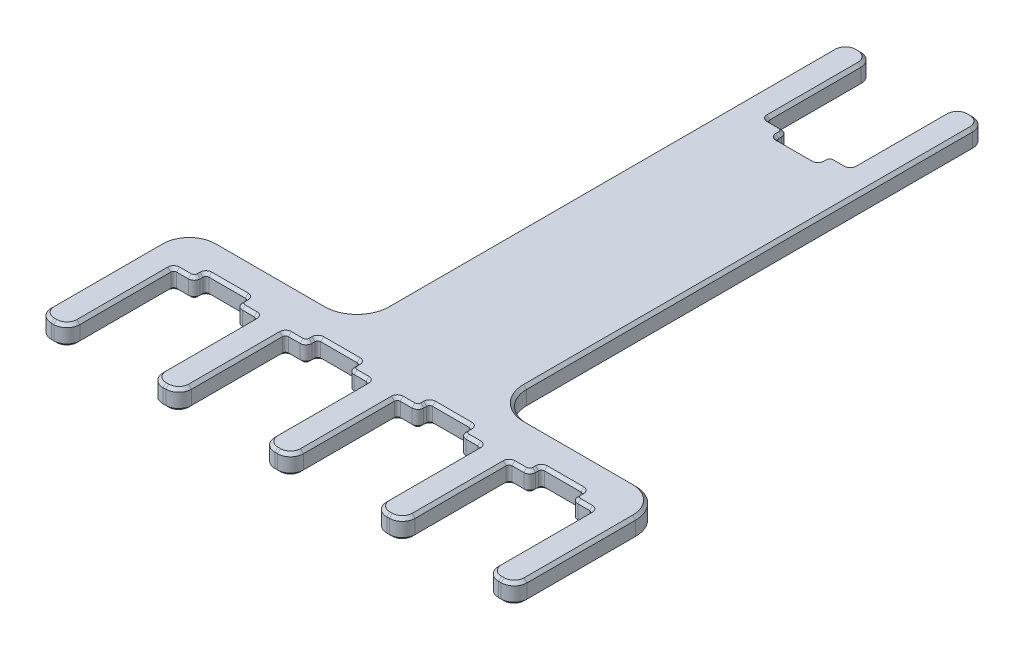
SolidWorks part; units mm, degrees
ref_plane "Front Plane" through (0, 0, 0) normal (0, 0, 1) x (1, 0, 0)
ref_plane "Top Plane" through (0, 0, 0) normal (0, 1, 0) x (1, 0, 0)
ref_plane "Right Plane" through (0, 0, 0) normal (1, 0, 0) x (0, 0, -1)
sketch "Sketch2" plane through (0, 0, 0) normal (0, 1, 0) x (1, 0, 0)
  line L0 (-5.2417, -1.575) -> (8.9583, -1.575)
  line L1 (-24.2917, -1.575) -> (-10.0917, -1.575)
  line L2 (-24.2917, -1.575) -> (-24.2917, -15.775)
  line L3 (-24.2917, -15.775) -> (-10.0917, -15.775)
  line L4 (-10.0917, -1.575) -> (-10.0917, -15.775)
  line L17 (-5.2417, -1.575) -> (-5.2417, -15.775)
  line L18 (-5.2417, -15.775) -> (8.9583, -15.775)
  line L19 (8.9583, -1.575) -> (8.9583, -15.775)
  line L20 (13.8083, -1.575) -> (28.0083, -1.575)
  line L21 (13.8083, -1.575) -> (13.8083, -15.775)
  line L22 (13.8083, -15.775) -> (28.0083, -15.775)
  line L23 (28.0083, -1.575) -> (28.0083, -15.775)
  line L24 (32.8583, -1.575) -> (47.0583, -1.575)
  line L25 (32.8583, -1.575) -> (32.8583, -15.775)
  line L26 (32.8583, -15.775) -> (47.0583, -15.775)
  line L27 (47.0583, -1.575) -> (47.0583, -15.775)
  line L28 (1.8583, -1.575) -> (1.8583, -15.775) construction
  line L29 (-17.1917, -15.775) -> (-17.1917, -1.575) construction
  dimension "D1" = 14.2
  dimension "D3" = 19.05
  dimension "D2" = 4
sketch "Sketch1" plane through (0, 0, 0) normal (0, 1, 0) x (1, 0, 0)
  line L0 (-29.1417, 5.925) -> (-0.5667, 5.925)
  line L1 (-0.5667, 5.925) -> (-0.5667, 89.125)
  line L3 (23.3333, 89.125) -> (23.3333, 5.925)
  line L4 (23.3333, 5.925) -> (51.9083, 5.925)
  line L5 (51.9083, 5.925) -> (51.9083, -19.775)
  line L6 (51.9083, -19.775) -> (-29.1417, -19.775)
  line L7 (-29.1417, -19.775) -> (-29.1417, 5.925)
  line L8 (-5.2417, -8.675) -> (-10.0917, -8.675) construction
  line L9 (-5.2417, -1.575) -> (-5.2417, -15.775) construction
  line L10 (-10.0917, -1.575) -> (-10.0917, -15.775) construction
  line L11 (47.0583, -8.675) -> (51.9083, -8.675) construction
  line L12 (47.0583, -1.575) -> (47.0583, -15.775) construction
  line L13 (-24.2917, -8.675) -> (-29.1417, -8.675) construction
  line L14 (-24.2917, -1.575) -> (-24.2917, -15.775) construction
  line L15 (18.4833, 70.925) -> (23.3333, 70.925) construction
  line L17 (-17.1917, -1.575) -> (-17.1917, -19.775) construction
  line L19 (-24.2917, -15.775) -> (-10.0917, -15.775) construction
  line L20 (-24.2917, -1.575) -> (-10.0917, -1.575) construction
  line L21 (4.2833, 89.125) -> (4.2833, 70.925)
  line L22 (4.2833, 70.925) -> (18.4833, 70.925)
  line L23 (18.4833, 70.925) -> (18.4833, 89.125)
  line L24 (-0.5667, 89.125) -> (4.2833, 89.125)
  line L25 (18.4833, 89.125) -> (23.3333, 89.125)
  line L26 (13.8083, -1.575) -> (28.0083, -1.575) construction
  line L27 (8.9583, -8.675) -> (13.8083, -8.675) construction
  line L28 (8.9583, -1.575) -> (8.9583, -15.775) construction
  line L29 (13.8083, -1.575) -> (13.8083, -15.775) construction
  line L30 (11.3833, 70.925) -> (11.3833, 89.125) construction
  line L31 (11.3833, -8.675) -> (11.3833, 70.925) construction
  line L32 (4.2833, 89.125) -> (18.4833, 89.125) construction
  dimension "D1" = 4
  dimension "D2" = 7.5
  dimension "D3" = 65
extrude "Boss-Extrude1" add sketch "Sketch1" along normal blind 3.4
sketch "Sketch3" plane through (0, 3.4, 0) normal (0, 1, 0) x (1, 0, 0)
  line L0 (-29.1417, -19.775) -> (51.9083, -19.775) construction
  line L2 (-24.2917, -1.575) -> (-24.2917, -19.775)
  line L3 (-24.2917, -19.775) -> (-10.0917, -19.775)
  line L4 (-10.0917, -1.575) -> (-10.0917, -19.775)
  line L5 (32.8583, -15.775) -> (47.0583, -15.775) construction
  line L7 (-5.2417, -1.575) -> (-5.2417, -19.775)
  line L8 (-5.2417, -19.775) -> (8.9583, -19.775)
  line L9 (8.9583, -1.575) -> (8.9583, -19.775)
  line L11 (13.8083, -1.575) -> (13.8083, -19.775)
  line L12 (13.8083, -19.775) -> (28.0083, -19.775)
  line L13 (28.0083, -1.575) -> (28.0083, -19.775)
  line L15 (32.8583, -1.575) -> (32.8583, -19.775)
  line L16 (32.8583, -19.775) -> (47.0583, -19.775)
  line L17 (47.0583, -1.575) -> (47.0583, -19.775)
  line L18 (-24.2917, -1.575) -> (-20.7917, -1.575)
  line L19 (-20.7917, -1.575) -> (-20.7917, 0.425)
  line L20 (-20.7917, 0.425) -> (-13.5917, 0.425)
  line L21 (-13.5917, 0.425) -> (-13.5917, -1.575)
  line L22 (-13.5917, -1.575) -> (-10.0917, -1.575)
  line L23 (-5.2417, -1.575) -> (-1.7417, -1.575)
  line L24 (-1.7417, -1.575) -> (-1.7417, 0.425)
  line L25 (-1.7417, 0.425) -> (5.4583, 0.425)
  line L26 (5.4583, 0.425) -> (5.4583, -1.575)
  line L27 (5.4583, -1.575) -> (8.9583, -1.575)
  line L28 (13.8083, -1.575) -> (17.3083, -1.575)
  line L29 (17.3083, -1.575) -> (17.3083, 0.425)
  line L30 (17.3083, 0.425) -> (24.5083, 0.425)
  line L31 (24.5083, 0.425) -> (24.5083, -1.575)
  line L32 (24.5083, -1.575) -> (28.0083, -1.575)
  line L33 (32.8583, -1.575) -> (36.3583, -1.575)
  line L34 (36.3583, -1.575) -> (36.3583, 0.425)
  line L35 (36.3583, 0.425) -> (43.5583, 0.425)
  line L36 (43.5583, 0.425) -> (43.5583, -1.575)
  line L37 (43.5583, -1.575) -> (47.0583, -1.575)
  line L38 (7.7833, 70.925) -> (7.7833, 68.925)
  line L39 (18.4833, 70.925) -> (4.2833, 70.925) construction
  line L40 (7.7833, 68.925) -> (14.9833, 68.925)
  line L41 (14.9833, 68.925) -> (14.9833, 70.925)
  line L42 (7.7833, 70.925) -> (14.9833, 70.925)
  line L43 (4.2833, 70.925) -> (7.7833, 70.925) construction
  line L44 (14.9833, 70.925) -> (18.4833, 70.925) construction
  dimension "D1" = 3.5
  dimension "D2" = 2
extrude "Cut-Extrude1" cut sketch "Sketch3" against normal blind 3.4
fillet "Fillet1" radius 5 4 edges at (-29.1417, 1.7, -5.925) (51.9083, 1.7, -5.925) (23.3333, 1.7, -5.925) (-0.5667, 1.7, -5.925)
fillet "Fillet2" radius 2.2 14 edges at (-0.5667, 1.7, -89.125) (4.2833, 1.7, -89.125) (18.4833, 1.7, -89.125) (23.3333, 1.7, -89.125) (51.9083, 1.7, 19.775) (47.0583, 1.7, 19.775) (32.8583, 1.7, 19.775) (28.0083, 1.7, 19.775) (13.8083, 1.7, 19.775) (8.9583, 1.7, 19.775) (-5.2417, 1.7, 19.775) (-10.0917, 1.7, 19.775) (-24.2917, 1.7, 19.775) (-29.1417, 1.7, 19.775)
fillet "Fillet3" radius 0.5 20 edges at (17.3083, 1.7, -0.425) (-1.7417, 1.7, -0.425) (-20.7917, 1.7, -0.425) (-13.5917, 1.7, -0.425) (5.4583, 1.7, -0.425) (24.5083, 1.7, -0.425) (36.3583, 1.7, -0.425) (43.5583, 1.7, -0.425) (47.0583, 1.7, 1.575) (32.8583, 1.7, 1.575) (13.8083, 1.7, 1.575) (28.0083, 1.7, 1.575) (8.9583, 1.7, 1.575) (-5.2417, 1.7, 1.575) (-10.0917, 1.7, 1.575) (-24.2917, 1.7, 1.575) (7.7833, 1.7, -68.925) (14.9833, 1.7, -68.925) (18.4833, 1.7, -70.925) (4.2833, 1.7, -70.925)
fillet "Fillet4" radius 1 10 edges at (-13.5917, 1.7, 1.575) (-1.7417, 1.7, 1.575) (5.4583, 1.7, 1.575) (17.3083, 1.7, 1.575) (24.5083, 1.7, 1.575) (36.3583, 1.7, 1.575) (43.5583, 1.7, 1.575) (-20.7917, 1.7, 1.575) (14.9833, 1.7, -70.925) (7.7833, 1.7, -70.925)
chamfer "Chamfer1" distance 0.5 192 edges at (-1.7417, 0, 0.325) (-1.5952, 0, -0.2786) (-2.0346, 0, 1.2821) (1.8583, 0, -0.425) (-3.7417, 0, 1.575) (5.3119, 0, -0.2786) (-5.0952, 0, 1.7214) (5.4583, 0, 0.325) (-5.2417, 0, 9.825) (5.7512, 0, 1.2821) (-5.886, 0, 19.1306) (7.4583, 0, 1.575) (-7.6667, 0, 19.775) (8.8119, 0, 1.7214) (-9.4473, 0, 19.1306) (8.9583, 0, 9.825) (-10.0917, 0, 9.825) (9.6027, 0, 19.1306) (-10.2381, 0, 1.7214) (11.3833, 0, 19.775) (-11.5917, 0, 1.575) (13.164, 0, 19.1306) (-13.2988, 0, 1.2821) (13.8083, 0, 9.825) (-13.5917, 0, 0.325) (13.9548, 0, 1.7214) (-13.7381, 0, -0.2786) (15.3083, 0, 1.575) (-17.1917, 0, -0.425) (17.0154, 0, 1.2821) (-20.6452, 0, -0.2786) (17.3083, 0, 0.325) (-20.7917, 0, 0.325) (17.4548, 0, -0.2786) (-21.0846, 0, 1.2821) (20.9083, 0, -0.425) (-22.7917, 0, 1.575) (24.3619, 0, -0.2786) (-24.1452, 0, 1.7214) (24.5083, 0, 0.325) (-24.2917, 0, 9.825) (24.8012, 0, 1.2821) (-24.936, 0, 19.1306) (26.5083, 0, 1.575) (-26.7167, 0, 19.775) (27.8619, 0, 1.7214) (-28.4973, 0, 19.1306) (28.0083, 0, 9.825) (-29.1417, 0, 8.325) (28.6527, 0, 19.1306) (-27.6772, 0, -4.4605) (30.4333, 0, 19.775) (-14.8542, 0, -5.925) (32.214, 0, 19.1306) (-2.0311, 0, -7.3895) (32.8583, 0, 9.825) (-0.5667, 0, -48.925) (33.0048, 0, 1.7214) (0.0777, 0, -88.4806) (34.3583, 0, 1.575) (1.8583, 0, -89.125) (36.0654, 0, 1.2821) (3.639, 0, -88.4806) (36.3583, 0, 0.325) (4.2833, 0, -79.175) (36.5048, 0, -0.2786) (4.4298, 0, -71.0714) (39.9583, 0, -0.425) (5.7833, 0, -70.925) (43.4119, 0, -0.2786) (7.4904, 0, -70.6321) (43.5583, 0, 0.325) (7.7833, 0, -69.675) (43.8512, 0, 1.2821) (7.9298, 0, -69.0714) (45.5583, 0, 1.575) (11.3833, 0, -68.925) (46.9119, 0, 1.7214) (14.8369, 0, -69.0714) (47.0583, 0, 9.825) (14.9833, 0, -69.675) (47.7027, 0, 19.1306) (15.2762, 0, -70.6321) (49.4833, 0, 19.775) (16.9833, 0, -70.925) (51.264, 0, 19.1306) (18.3369, 0, -71.0714) (51.9083, 0, 8.325) (18.4833, 0, -79.175) (50.4439, 0, -4.4605) (19.1277, 0, -88.4806) (37.6208, 0, -5.925) (20.9083, 0, -89.125) (24.7978, 0, -7.3895) (22.689, 0, -88.4806) (23.3333, 0, -48.925) (-1.7417, 3.4, 0.325) (-1.5952, 3.4, -0.2786) (-2.0346, 3.4, 1.2821) (1.8583, 3.4, -0.425) (-3.7417, 3.4, 1.575) (5.3119, 3.4, -0.2786) (-5.0952, 3.4, 1.7214) (5.4583, 3.4, 0.325) (-5.2417, 3.4, 9.825) (5.7512, 3.4, 1.2821) (-5.886, 3.4, 19.1306) (7.4583, 3.4, 1.575) (-7.6667, 3.4, 19.775) (8.8119, 3.4, 1.7214) (-9.4473, 3.4, 19.1306) (8.9583, 3.4, 9.825) (-10.0917, 3.4, 9.825) (9.6027, 3.4, 19.1306) (-10.2381, 3.4, 1.7214) (11.3833, 3.4, 19.775) (-11.5917, 3.4, 1.575) (13.164, 3.4, 19.1306) (-13.2988, 3.4, 1.2821) (13.8083, 3.4, 9.825) (-13.5917, 3.4, 0.325) (13.9548, 3.4, 1.7214) (-13.7381, 3.4, -0.2786) (15.3083, 3.4, 1.575) (-17.1917, 3.4, -0.425) (17.0154, 3.4, 1.2821) (-20.6452, 3.4, -0.2786) (17.3083, 3.4, 0.325) (-20.7917, 3.4, 0.325) (17.4548, 3.4, -0.2786) (-21.0846, 3.4, 1.2821) (20.9083, 3.4, -0.425) (-22.7917, 3.4, 1.575) (24.3619, 3.4, -0.2786) (-24.1452, 3.4, 1.7214) (24.5083, 3.4, 0.325) (-24.2917, 3.4, 9.825) (24.8012, 3.4, 1.2821) (-24.936, 3.4, 19.1306) (26.5083, 3.4, 1.575) (-26.7167, 3.4, 19.775) (27.8619, 3.4, 1.7214) (-28.4973, 3.4, 19.1306) (28.0083, 3.4, 9.825) (-29.1417, 3.4, 8.325) (28.6527, 3.4, 19.1306) (-27.6772, 3.4, -4.4605) (30.4333, 3.4, 19.775) (-14.8542, 3.4, -5.925) (32.214, 3.4, 19.1306) (-2.0311, 3.4, -7.3895) (32.8583, 3.4, 9.825) (-0.5667, 3.4, -48.925) (33.0048, 3.4, 1.7214) (0.0777, 3.4, -88.4806) (34.3583, 3.4, 1.575) (1.8583, 3.4, -89.125) (36.0654, 3.4, 1.2821) (3.639, 3.4, -88.4806) (36.3583, 3.4, 0.325) (4.2833, 3.4, -79.175) (36.5048, 3.4, -0.2786) (4.4298, 3.4, -71.0714) (39.9583, 3.4, -0.425) (5.7833, 3.4, -70.925) (43.4119, 3.4, -0.2786) (7.4904, 3.4, -70.6321) (43.5583, 3.4, 0.325) (7.7833, 3.4, -69.675) (43.8512, 3.4, 1.2821) (7.9298, 3.4, -69.0714) (45.5583, 3.4, 1.575) (11.3833, 3.4, -68.925) (46.9119, 3.4, 1.7214) (14.8369, 3.4, -69.0714) (47.0583, 3.4, 9.825) (14.9833, 3.4, -69.675) (47.7027, 3.4, 19.1306) (15.2762, 3.4, -70.6321) (49.4833, 3.4, 19.775) (16.9833, 3.4, -70.925) (51.264, 3.4, 19.1306) (18.3369, 3.4, -71.0714) (51.9083, 3.4, 8.325) (18.4833, 3.4, -79.175) (50.4439, 3.4, -4.4605) (19.1277, 3.4, -88.4806) (37.6208, 3.4, -5.925) (20.9083, 3.4, -89.125) (24.7978, 3.4, -7.3895) (22.689, 3.4, -88.4806) (23.3333, 3.4, -48.925)
